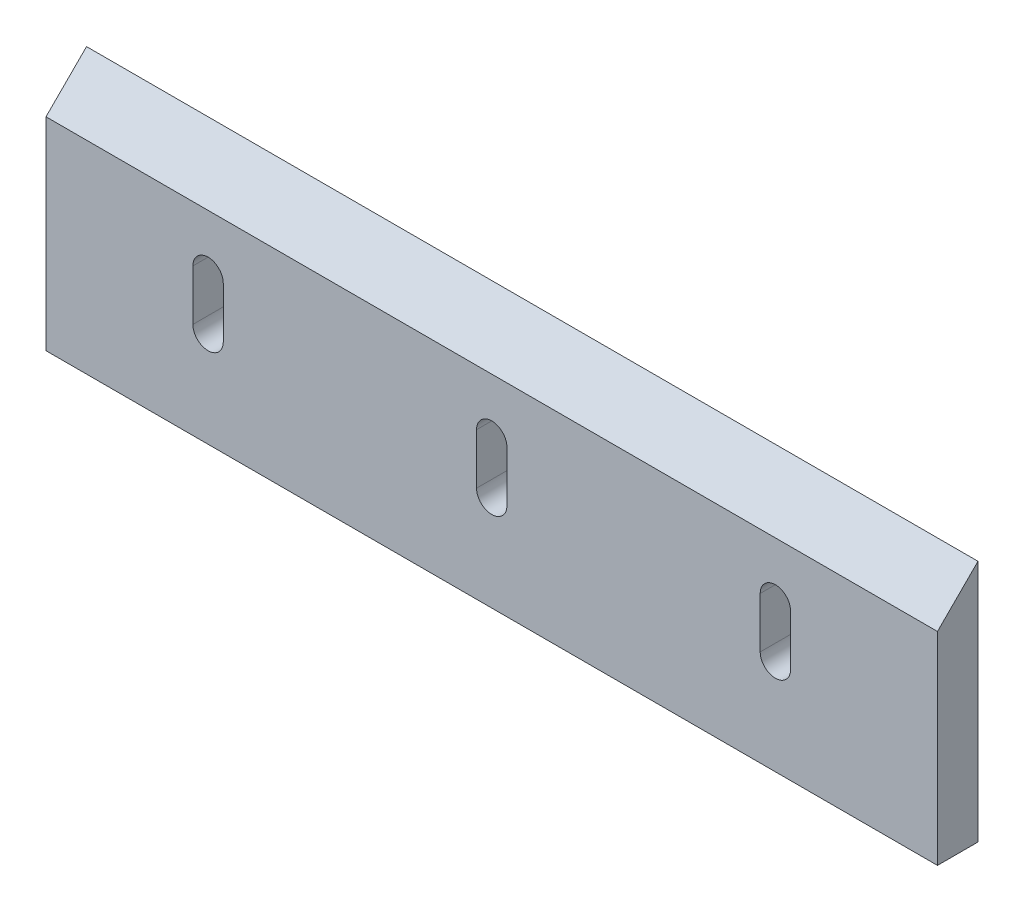
SolidWorks part; units mm, degrees
ref_plane "Front Plane" through (0, 0, 0) normal (0, 0, 1) x (1, 0, 0)
ref_plane "Top Plane" through (0, 0, 0) normal (0, 1, 0) x (1, 0, 0)
ref_plane "Right Plane" through (0, 0, 0) normal (1, 0, 0) x (0, 0, -1)
sketch "Sketch1" plane through (0, 0, 0) normal (0, 0, 1) x (1, 0, 0)
  line L1 (-139.7, -38.1) -> (139.7, -38.1)
  line L2 (-139.7, -38.1) -> (-139.7, 38.1)
  line L3 (-139.7, 38.1) -> (139.7, 38.1)
  line L4 (139.7, -38.1) -> (139.7, 38.1)
  line L5 (-139.7, -38.1) -> (139.7, 38.1) construction
  line L6 (-139.7, 38.1) -> (139.7, -38.1) construction
  point P0 (0, 0)
  dimension "D1" = 76.2
  dimension "D2" = 279.4
extrude "Boss-Extrude1" add sketch "Sketch1" along normal mid plane 12.7
sketch "Sketch2" plane through (0, 0, 0) normal (1, 0, 0) x (0, 0, -1)
  line L0 (-138.035, 0) -> (138.035, 0) construction
  line L1 (0, -131.52) -> (0, 131.52) construction
  line L2 (6.35, 38.1) -> (-6.35, 25.4)
  line L3 (6.35, 38.1) -> (6.35, 25.4) construction
  line L5 (-6.35, 25.4) -> (6.35, 25.4) construction
  line L6 (-6.35, -38.1) -> (-6.35, 38.1) construction
  line L7 (6.35, 38.1) -> (-6.35, 38.1)
  line L8 (-6.35, 25.4) -> (-6.35, 38.1)
  point P4 (0, 0)
  point P8 (0, 0)
  dimension "D1" = 45
  dimension "D2" = 12.7
extrude "Cut-Extrude2" cut sketch "Sketch2" against normal mid plane 279.4
sketch "Sketch3" plane through (0, 0, 0) normal (0, 0, 1) x (1, 0, 0)
  line L0 (195.8297, 0) -> (-195.8297, 0) construction
  line L1 (0, -109.3707) -> (0, 109.3707) construction
  line L2 (88.9, -7.9375) -> (88.9, 7.9375) construction
  line L4 (84.1375, -7.9375) -> (84.1375, 7.9375)
  line L5 (93.6625, -7.9375) -> (93.6625, 7.9375)
  line L6 (0, -7.9375) -> (0, 7.9375) construction
  line L7 (-4.7625, -7.9375) -> (-4.7625, 7.9375)
  line L8 (4.7625, -7.9375) -> (4.7625, 7.9375)
  line L9 (-88.9, -7.9375) -> (-88.9, 7.9375) construction
  line L10 (-93.6625, -7.9375) -> (-93.6625, 7.9375)
  line L11 (-84.1375, -7.9375) -> (-84.1375, 7.9375)
  arc A6 (84.1375, -7.9375) -> (93.6625, -7.9375) centre (88.9, -7.9375) ccw
  arc A7 (93.6625, 7.9375) -> (84.1375, 7.9375) centre (88.9, 7.9375) ccw
  arc A8 (-4.7625, -7.9375) -> (4.7625, -7.9375) centre (0, -7.9375) ccw
  arc A9 (4.7625, 7.9375) -> (-4.7625, 7.9375) centre (0, 7.9375) ccw
  arc A10 (-93.6625, -7.9375) -> (-84.1375, -7.9375) centre (-88.9, -7.9375) ccw
  arc A11 (-84.1375, 7.9375) -> (-93.6625, 7.9375) centre (-88.9, 7.9375) ccw
  point P4 (0, 0)
  point P8 (0, 0)
  point P12 (0, 0)
  point P15 (88.9, 0)
  point P25 (-88.9, 0)
  dimension "D1" = 9.525
  dimension "D2" = 3
extrude "Cut-Extrude3" cut sketch "Sketch3" against normal mid plane 76.2
